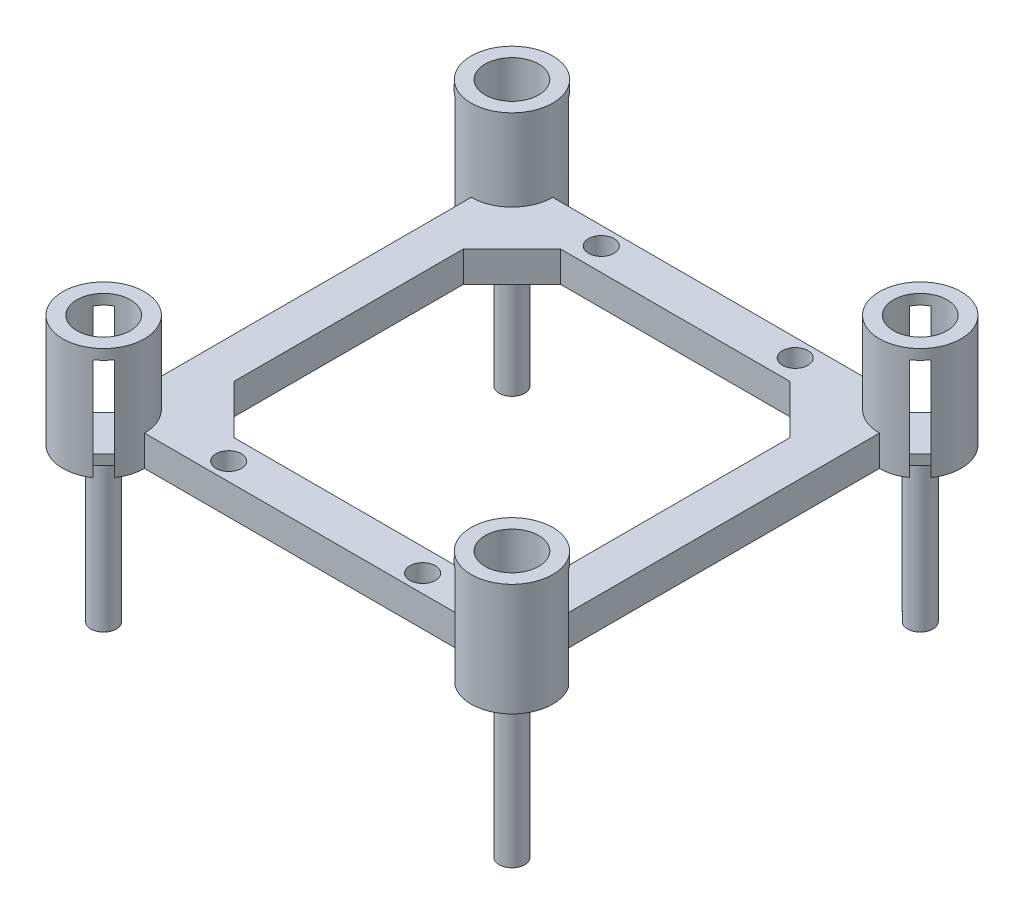
SolidWorks part; units mm, degrees
ref_plane "Front Plane" through (0, 0, 0) normal (0, 0, 1) x (1, 0, 0)
ref_plane "Top Plane" through (0, 0, 0) normal (0, 1, 0) x (1, 0, 0)
ref_plane "Right Plane" through (0, 0, 0) normal (1, 0, 0) x (0, 0, -1)
sketch "Sketch1" plane through (0, 0, 0) normal (0, 1, 0) x (1, 0, 0)
  line L0 (-22.5, 32) -> (22.5, 32)
  line L13 (-32, -40) -> (32, -40)
  line L14 (-40, -32) -> (-40, 32)
  line L15 (-32, 40) -> (32, 40)
  line L16 (40, -32) -> (40, 32)
  line L17 (-22.5, -32) -> (22.5, -32)
  line L18 (-32, 22.5) -> (-32, -22.5)
  line L19 (32, 22.5) -> (32, -22.5)
  line L20 (-22.5, 32) -> (-32, 22.5)
  line L21 (-32, -22.5) -> (-22.5, -32)
  line L22 (22.5, -32) -> (32, -22.5)
  line L23 (32, 22.5) -> (22.5, 32)
  circle A0 centre (-19, 36.5) radius 2.5
  circle A1 centre (19, 36.5) radius 2.5
  circle A2 centre (-19, -36.5) radius 2.5
  circle A3 centre (19, -36.5) radius 2.5
  arc A4 (40, 32) -> (32, 40) centre (40, 40) ccw
  arc A5 (32, -40) -> (40, -32) centre (40, -40) ccw
  arc A6 (-32, 40) -> (-40, 32) centre (-40, 40) ccw
  arc A7 (-40, -32) -> (-32, -40) centre (-40, -40) ccw
  dimension "D5" = 22.5
  dimension "D8" = 5
  dimension "D10" = 16
  dimension "D11" = 22.5
  dimension "D1" = 38
  dimension "D2" = 73
  dimension "D3" = 19
  dimension "D4" = 80
  dimension "D6" = 22.5
  dimension "D7" = 8
  dimension "D9" = 80
  dimension "D12" = 45
  dimension "D13" = 22.5
  dimension "D14" = 8
  dimension "D15" = 8
  dimension "D16" = 40
  dimension "D17" = 40
  dimension "D18" = 32
  dimension "D19" = 80
extrude "Boss-Extrude1" add sketch "Sketch1" along normal blind 6 contours A6 L14 A7 L13 A5 L16 A4 L15 | L23 L0 L20 L18 L21 L17 L22 L19
sketch "Sketch2" plane through (0, 0, 0) normal (0, -1, 0) x (1, 0, 0)
  circle A0 centre (-19, -36.5) radius 2.5 construction
  circle A1 centre (19, -36.5) radius 2.5 construction
  circle A2 centre (19, 36.5) radius 2.5 construction
  circle A3 centre (-19, 36.5) radius 2.5 construction
  circle A4 centre (-19, -36.5) radius 2.5
  circle A5 centre (19, -36.5) radius 2.5
  circle A6 centre (19, 36.5) radius 2.5
  circle A7 centre (-19, 36.5) radius 2.5
extrude "Cut-Extrude1" cut sketch "Sketch2" against normal through all
sketch "Sketch4" plane through (0, 6, 0) normal (0, 1, 0) x (1, 0, 0)
  circle A0 centre (-40, 40) radius 5.25
  circle A1 centre (-40, 40) radius 8
  circle A2 centre (40, 40) radius 5.25
  circle A3 centre (40, 40) radius 8
  circle A4 centre (40, -40) radius 5.25
  circle A5 centre (40, -40) radius 8
  circle A6 centre (-40, -40) radius 5.25
  circle A7 centre (-40, -40) radius 8
  dimension "D1" = 10.5
  dimension "D2" = 16
extrude "Boss-Extrude2" add sketch "Sketch4" along normal blind 16 and the other way blind 4 contours A3 | A1 | A7 | A5
sketch "Sketch5" plane through (0, 0, 0) normal (0, -1, 0) x (1, 0, 0)
  line L0 (-45.6569, 34.3431) -> (-34.3431, 45.6569) construction
  line L1 (-32, 22.5) -> (-22.5, 32) construction
  line L2 (34.3431, 45.6569) -> (45.6569, 34.3431) construction
  line L3 (22.5, 32) -> (32, 22.5) construction
  line L4 (34.3431, -45.6569) -> (45.6569, -34.3431) construction
  line L5 (32, -22.5) -> (22.5, -32) construction
  line L6 (-34.7141, -46.005) -> (-45.2859, -33.995) construction
  line L9 (-37.5251, 44.5962) -> (-35.5041, 46.6172)
  line L10 (-37.5251, 44.5962) -> (-35.4038, 42.4749)
  line L12 (-35.4038, 42.4749) -> (-33.3828, 44.4959)
  line L13 (-37.5251, 44.5962) -> (-33.4521, 44.5962) construction
  line L14 (-35.4038, 46.5479) -> (-35.4038, 42.4749) construction
  line L15 (-40, 40) -> (-45.6569, 45.6569) construction
  line L16 (-46.5479, 35.4038) -> (-42.4749, 35.4038) construction
  line L17 (-44.5962, 37.5251) -> (-44.5962, 33.4521) construction
  line L18 (-42.4749, 35.4038) -> (-44.4959, 33.3828)
  line L19 (-44.5962, 37.5251) -> (-42.4749, 35.4038)
  line L20 (-44.5962, 37.5251) -> (-46.6172, 35.5041)
  line L21 (-40, 40) -> (40, -40) construction
  line L22 (40, 40) -> (-40, -40) construction
  line L23 (37.5251, 44.5962) -> (35.5041, 46.6172)
  line L24 (37.5251, 44.5962) -> (35.4038, 42.4749)
  line L26 (35.4038, 42.4749) -> (33.3828, 44.4959)
  line L27 (37.5251, 44.5962) -> (33.4521, 44.5962) construction
  line L28 (35.4038, 46.5479) -> (35.4038, 42.4749) construction
  line L29 (46.5479, 35.4038) -> (42.4749, 35.4038) construction
  line L30 (44.5962, 37.5251) -> (44.5962, 33.4521) construction
  line L31 (42.4749, 35.4038) -> (44.4959, 33.3828)
  line L32 (44.5962, 37.5251) -> (42.4749, 35.4038)
  line L33 (44.5962, 37.5251) -> (46.6172, 35.5041)
  line L34 (37.5251, -44.5962) -> (33.4521, -44.5962) construction
  line L35 (35.4038, -46.5479) -> (35.4038, -42.4749) construction
  line L36 (40, -40) -> (45.6569, -45.6569) construction
  line L37 (46.5479, -35.4038) -> (42.4749, -35.4038) construction
  line L38 (44.5962, -37.5251) -> (44.5962, -33.4521) construction
  line L39 (34.3431, -45.6569) -> (45.6569, -34.3431) construction
  line L40 (37.5251, -44.5962) -> (35.5041, -46.6172)
  line L41 (37.5251, -44.5962) -> (35.4038, -42.4749)
  line L42 (35.4038, -42.4749) -> (33.3828, -44.4959)
  line L43 (42.4749, -35.4038) -> (44.4959, -33.3828)
  line L44 (44.5962, -37.5251) -> (42.4749, -35.4038)
  line L45 (44.5962, -37.5251) -> (46.6172, -35.5041)
  line L46 (-37.5251, -44.5962) -> (-33.4521, -44.5962) construction
  line L47 (-35.4038, -46.5479) -> (-35.4038, -42.4749) construction
  line L48 (-46.5479, -35.4038) -> (-42.4749, -35.4038) construction
  line L49 (-44.5962, -37.5251) -> (-44.5962, -33.4521) construction
  line L50 (-45.6569, -34.3431) -> (-34.3431, -45.6569) construction
  line L51 (-37.5251, -44.5962) -> (-35.5041, -46.6172)
  line L52 (-37.5251, -44.5962) -> (-35.4038, -42.4749)
  line L53 (-35.4038, -42.4749) -> (-33.3828, -44.4959)
  line L54 (-42.4749, -35.4038) -> (-44.4959, -33.3828)
  line L55 (-44.5962, -37.5251) -> (-42.4749, -35.4038)
  line L56 (-44.5962, -37.5251) -> (-46.6172, -35.5041)
  arc A0 (-32, 40) -> (-40, 32) centre (-40, 40) ccw construction
  arc A1 (40, 32) -> (32, 40) centre (40, 40) ccw construction
  arc A2 (32, -40) -> (40, -32) centre (40, -40) ccw construction
  arc A3 (-40, -32) -> (-32, -40) centre (-40, -40) ccw construction
  arc A4 (-40, -32) -> (-32, -40) centre (-40, -40) ccw
  arc A5 (32, -40) -> (40, -32) centre (40, -40) ccw
  arc A6 (46.6172, 35.5041) -> (44.4959, 33.3828) centre (40, 40) cw
  arc A7 (-33.3828, 44.4959) -> (-35.5041, 46.6172) centre (-40, 40) ccw
  arc A8 (-44.4959, 33.3828) -> (-46.6172, 35.5041) centre (-40, 40) cw
  arc A9 (35.5041, 46.6172) -> (33.3828, 44.4959) centre (40, 40) ccw
  arc A10 (33.3828, -44.4959) -> (35.5041, -46.6172) centre (40, -40) ccw
  arc A11 (44.4959, -33.3828) -> (46.6172, -35.5041) centre (40, -40) cw
  arc A12 (-46.6172, -35.5041) -> (-44.4959, -33.3828) centre (-40, -40) cw
  arc A13 (-35.5041, -46.6172) -> (-33.3828, -44.4959) centre (-40, -40) ccw
  point P7 (-40, 40)
  point P17 (40, 40)
  point P27 (40, -40)
  point P34 (-40, -40)
  point P37 (-35.4038, 44.5962)
  point P48 (-44.5962, 35.4038)
  point P50 (35.4038, 44.5962)
  point P62 (44.5962, 35.4038)
  point P77 (35.4038, -44.5962)
  point P78 (44.5962, -35.4038)
  point P79 (40, -40)
  point P94 (-35.4038, -44.5962)
  point P95 (-44.5962, -35.4038)
  point P96 (-40, -40)
  arc M27 (32, -40) -> (40, -32) centre (40, -40) ccw
  arc M29 (40, 32) -> (32, 40) centre (40, 40) ccw
  arc M31 (-32, 40) -> (-40, 32) centre (-40, 40) ccw
  arc M33 (-40, -32) -> (-32, -40) centre (-40, -40) ccw
  dimension "D2" = 3
extrude "Cut-Extrude2" cut sketch "Sketch5" against normal blind 20 contours L10 L12 L9 M31 | L19 L20 L18 M31 | L26 L24 L23 M29 | L33 L32 L31 M29 | L44 L45 L43 M27 | L41 L42 L40 M27 | L56 L55 L54 M33 | L53 L52 L51 M33
sketch "Sketch7" plane through (0, 22, 0) normal (0, 1, 0) x (1, 0, 0)
  circle A0 centre (40, 40) radius 5.25
  circle A1 centre (40, -40) radius 5.25
  circle A2 centre (-40, -40) radius 5.25
  circle A3 centre (-40, 40) radius 5.25
extrude "Cut-Extrude3" cut sketch "Sketch7" against normal blind 20
sketch "Sketch8" plane through (0, 0, 0) normal (0, -1, 0) x (1, 0, 0)
  circle A0 centre (-40, 40) radius 2.5
  circle A1 centre (40, 40) radius 2.5
  circle A2 centre (40, -40) radius 2.5
  circle A3 centre (-40, -40) radius 2.5
  dimension "D1" = 5
extrude "Boss-Extrude3" add sketch "Sketch8" along normal blind 30
